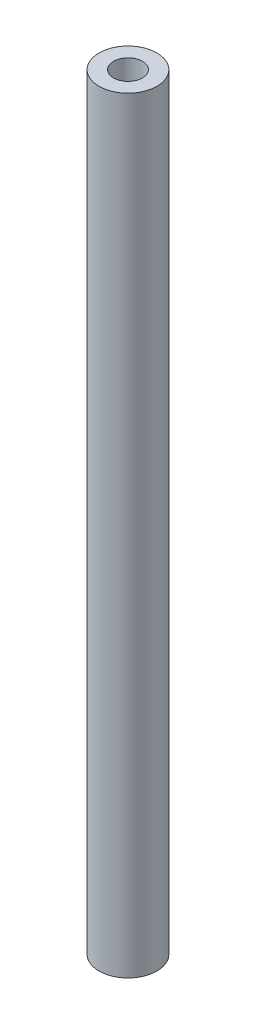
SolidWorks part; units mm, degrees
material "PTFE (general)"
ref_plane "Front" through (0, 0, 0) normal (0, 0, 1) x (1, 0, 0)
ref_plane "Top" through (0, 0, 0) normal (0, 1, 0) x (1, 0, 0)
ref_plane "Right" through (0, 0, 0) normal (1, 0, 0) x (0, 0, -1)
sketch "Sketch1" plane through (0, 0, 0) normal (0, 1, 0) x (1, 0, 0)
  circle A0 centre (0, 0) radius 2
  circle A1 centre (0, 0) radius 1
  dimension "D1" = 2
  dimension "D2" = 4
extrude "Boss-Extrude1" add sketch "Sketch1" along normal blind 53
